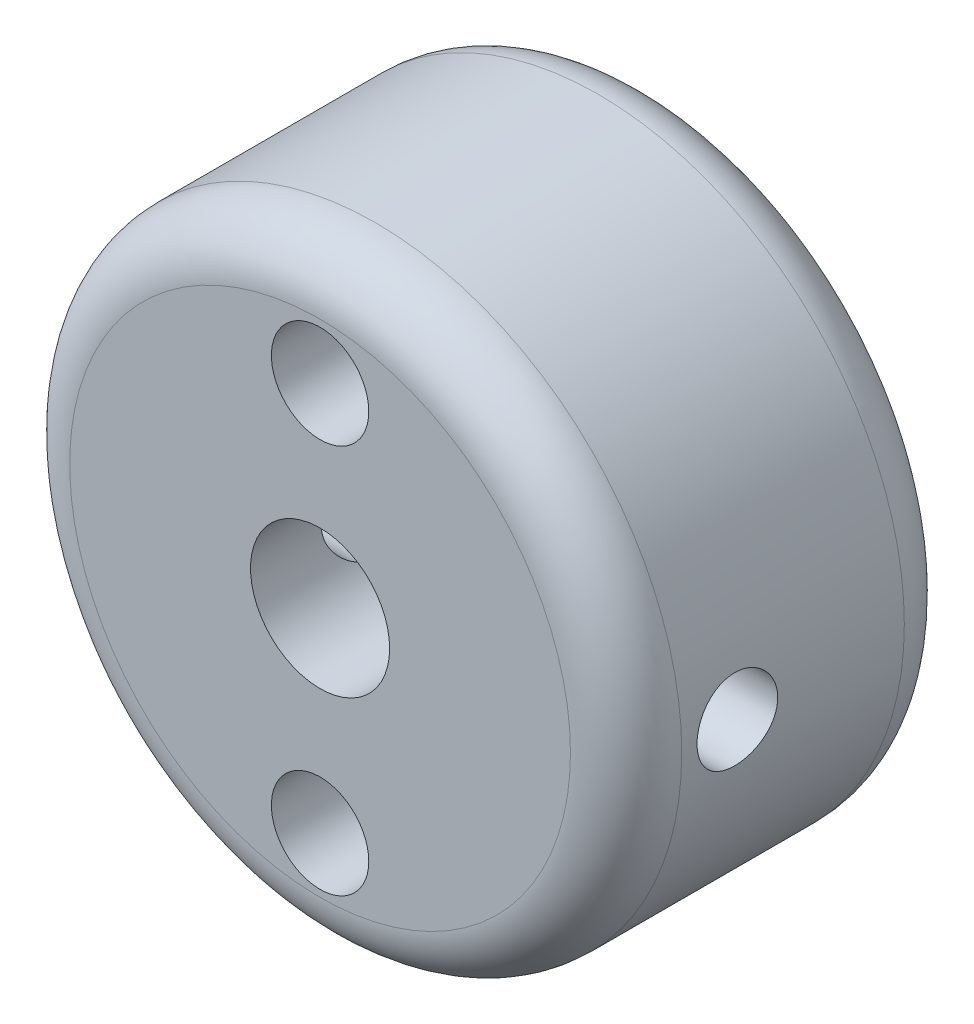
SolidWorks part; units mm, degrees
ref_plane "前视基准面" through (0, 0, 0) normal (0, 0, 1) x (1, 0, 0)
ref_plane "上视基准面" through (0, 0, 0) normal (0, 1, 0) x (1, 0, 0)
ref_plane "右视基准面" through (0, 0, 0) normal (1, 0, 0) x (0, 0, -1)
sketch "草图1" plane through (0, 0, 0) normal (0, 0, 1) x (1, 0, 0)
  circle A0 centre (0, 0) radius 11
  dimension "D1" = 22
extrude "凸台-拉伸1" add sketch "草图1" along normal blind 12
sketch "草图3" plane through (0, 0, 12) normal (0, 0, 1) x (1, 0, 0)
  circle A0 centre (0, 7) radius 1.75
  circle A1 centre (0, -7) radius 1.75
  dimension "D1" = 3.5
  dimension "D2" = 14
extrude "切除-拉伸1" cut sketch "草图3" against normal through all
sketch "草图4" plane through (0, 0, 12) normal (0, 0, 1) x (1, 0, 0)
  circle A0 centre (0, 0) radius 2.5
  dimension "D1" = 5
extrude "切除-拉伸2" cut sketch "草图4" against normal offset from surface (10 mm away) 2 up to face at (1.75, 7, 0)
sketch "草图5" plane through (0, 0, 0) normal (1, 0, 0) x (0, 0, -1)
  line L0 (-12, 11) -> (-12, -11) construction
  circle A0 centre (-8, 0) radius 1.45
  circle A1 centre (-2, 0) radius 1.45 construction
  dimension "D1" = 2.9
  dimension "D2" = 4
  dimension "D4" = 6
  dimension "D3" = 2
extrude "切除-拉伸3" cut sketch "草图5" against normal through all both and the other way through all
fillet "圆角1" radius 2 2 edges at (11, 0, 0) (11, 0, 12)
equation "\"4。5\"=4.3802"
